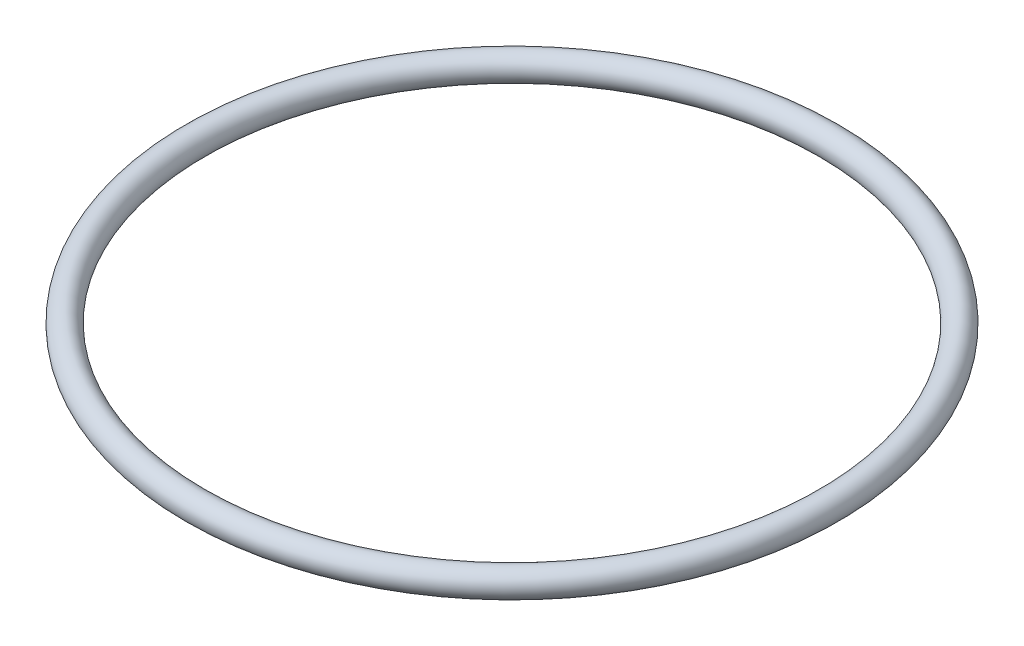
SolidWorks part; units mm, degrees
material "POLYURETHANE (11671)"
ref_plane "Front Plane" through (0, 0, 0) normal (0, 0, 1) x (1, 0, 0)
ref_plane "Top Plane" through (0, 0, 0) normal (0, 1, 0) x (1, 0, 0)
ref_plane "Right Plane" through (0, 0, 0) normal (1, 0, 0) x (0, 0, -1)
sketch "Sketch1" plane through (0, 0, 0) normal (0, 0, 1) x (1, 0, 0)
  line L0 (0, 0) -> (0, 7.8103) construction
  circle A0 centre (-12, 0) radius 0.5
  dimension "D1" = 1
  dimension "D2" = 23
revolve "Revolve1" add sketch "Sketch1" angle 360 about L0
